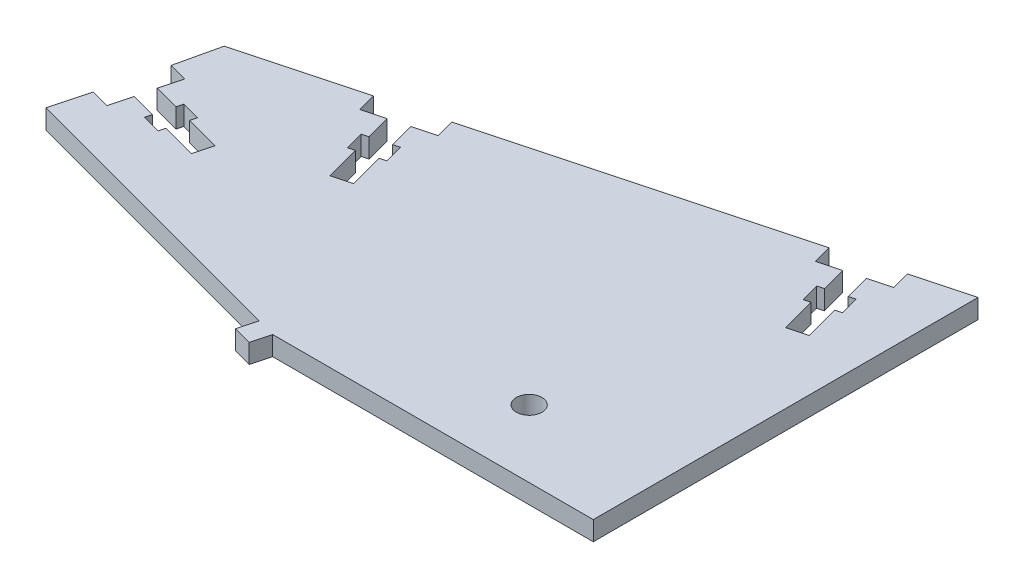
SolidWorks part; units mm, degrees
ref_plane "前视基准面" through (0, 0, 0) normal (0, 0, 1) x (1, 0, 0)
ref_plane "上视基准面" through (0, 0, 0) normal (0, 1, 0) x (1, 0, 0)
ref_plane "右视基准面" through (0, 0, 0) normal (1, 0, 0) x (0, 0, -1)
other "Configuration Table"
sketch "草图1" plane through (0, 0, 0) normal (0, 1, 0) x (1, 0, 0)
  line L0 (31.4659, 36.9106) -> (32.2424, 34.0129)
  line L1 (-9.8408, -20.76) -> (40.1592, -20.76)
  line L2 (40.1592, -20.76) -> (40.1592, 39.24)
  line L3 (40.1592, 39.24) -> (31.4659, 36.9106)
  line L5 (26.0332, 28.208) -> (26.9991, 28.4668)
  line L6 (25.9638, 32.3305) -> (26.9991, 28.4668)
  line L7 (29.8969, 29.2433) -> (30.8628, 29.5021)
  line L8 (30.8628, 29.5021) -> (31.6393, 26.6043)
  line L9 (31.6393, 26.6043) -> (30.6733, 26.3455)
  line L10 (30.6733, 26.3455) -> (32.1227, 20.9363)
  line L11 (32.1227, 20.9363) -> (29.225, 20.1599)
  line L12 (29.225, 20.1599) -> (27.7756, 25.5691)
  line L13 (27.7756, 25.5691) -> (26.8096, 25.3102)
  line L14 (26.8096, 25.3102) -> (26.0332, 28.208)
  line L15 (22.5831, 31.4247) -> (25.9638, 32.3305)
  line L16 (29.8969, 29.2433) -> (28.8616, 33.107)
  line L17 (28.8616, 33.107) -> (32.2424, 34.0129)
  line L18 (22.5831, 31.4247) -> (21.8066, 34.3225)
  line L19 (21.8066, 34.3225) -> (-24.5578, 21.8991)
  line L20 (21.8066, 34.3225) -> (-1.3756, 28.1108) construction
  line L21 (-1.3756, 28.1108) -> (-4.8675, 41.1429) construction
  line L22 (-34.2171, 19.311) -> (-33.4406, 16.4132)
  line L23 (-30.0599, 17.319) -> (-33.4406, 16.4132)
  line L24 (-29.0246, 13.4553) -> (-30.0599, 17.319)
  line L25 (-29.0246, 13.4553) -> (-29.9905, 13.1965)
  line L26 (-29.9905, 13.1965) -> (-29.2141, 10.2987)
  line L27 (-29.2141, 10.2987) -> (-28.2481, 10.5576)
  line L28 (-28.2481, 10.5576) -> (-26.7987, 5.1484)
  line L29 (-26.7987, 5.1484) -> (-23.901, 5.9248)
  line L30 (-25.3504, 11.334) -> (-24.3844, 11.5928)
  line L31 (-23.901, 5.9248) -> (-25.3504, 11.334)
  line L32 (-24.3844, 11.5928) -> (-25.1609, 14.4906)
  line L33 (-27.1621, 18.0955) -> (-26.1268, 14.2318)
  line L34 (-23.7813, 19.0014) -> (-24.5578, 21.8991)
  line L35 (-23.7813, 19.0014) -> (-27.1621, 18.0955)
  line L36 (-26.1268, 14.2318) -> (-25.1609, 14.4906)
  line L37 (40.1592, 39.24) -> (-45.0317, 16.4132) construction
  line L38 (-34.2171, 19.311) -> (-52.5697, 14.3934)
  line L39 (-9.8408, -20.76) -> (-55.5987, -8.4992) construction
  line L40 (-9.8408, -20.76) -> (-12.7385, -19.9835) construction
  line L41 (-12.7385, -19.9835) -> (-58.1371, -7.819)
  line L42 (-12.7385, -19.9835) -> (-13.515, -22.8813)
  line L43 (-13.515, -22.8813) -> (-10.6172, -23.6578)
  line L44 (-10.6172, -23.6578) -> (-9.8408, -20.76)
  line L45 (-58.1371, -7.819) -> (-56.5841, -2.0235)
  line L46 (-56.5841, -2.0235) -> (-53.6864, -2.7999)
  line L47 (-53.6864, -2.7999) -> (-52.7805, 0.5808)
  line L48 (-52.7805, 0.5808) -> (-48.9168, -0.4545)
  line L49 (-48.9168, -0.4545) -> (-49.1756, -1.4204)
  line L50 (-49.1756, -1.4204) -> (-46.2778, -2.1968)
  line L51 (-46.2778, -2.1968) -> (-46.019, -1.2309)
  line L52 (-46.019, -1.2309) -> (-40.6098, -2.6803)
  line L53 (-40.6098, -2.6803) -> (-39.8334, 0.2175)
  line L54 (-39.8334, 0.2175) -> (-45.2426, 1.6669)
  line L55 (-45.2426, 1.6669) -> (-44.9837, 2.6328)
  line L56 (-44.9837, 2.6328) -> (-47.8815, 3.4092)
  line L57 (-47.8815, 3.4092) -> (-48.1403, 2.4433)
  line L58 (-48.1403, 2.4433) -> (-52.12, 3.5096)
  line L59 (-52.12, 3.5096) -> (-51.2141, 6.8904)
  line L60 (-51.2141, 6.8904) -> (-54.1119, 7.6668)
  line L61 (-54.1119, 7.6668) -> (-52.5697, 14.3934)
  dimension "D15" = 4
  dimension "D1" = 60
  dimension "D2" = 50
  dimension "D3" = 3
  dimension "D4" = 5.6
  dimension "D5" = 5.6
  dimension "D6" = 3
  dimension "D7" = 3
  dimension "D8" = 3.5
  dimension "D9" = 3.5
  dimension "D10" = 1
  dimension "D11" = 1
  dimension "D12" = 9
  dimension "D13" = 3
  dimension "D14" = 3
  dimension "D16" = 4
  dimension "D17" = 4
extrude "凸台-拉伸1" add sketch "草图1" along normal blind 3
sketch "草图2" plane through (0, 3, 0) normal (0, 1, 0) x (1, 0, 0)
  circle A0 centre (19.6592, -10.26) radius 2
extrude "切除-拉伸1" cut sketch "草图2" against normal through all
